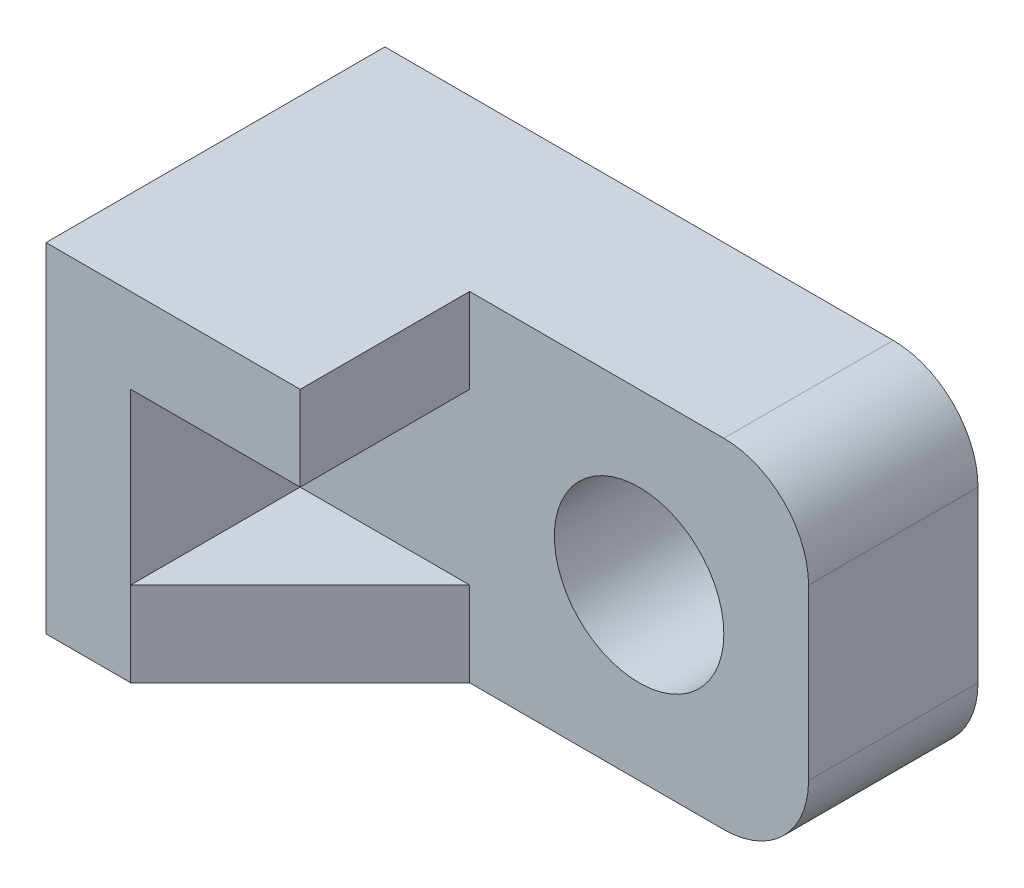
SolidWorks part; units mm, degrees
ref_plane "Front Plane" through (0, 0, 0) normal (0, 0, 1) x (1, 0, 0)
ref_plane "Top Plane" through (0, 0, 0) normal (0, 1, 0) x (1, 0, 0)
ref_plane "Right Plane" through (0, 0, 0) normal (1, 0, 0) x (0, 0, -1)
sketch "Sketch1" plane through (0, 0, 0) normal (0, 0, 1) x (1, 0, 0)
  line L0 (0, 20) -> (0, -20)
  line L1 (0, 20) -> (60, 20)
  line L2 (70, 10) -> (70, -10)
  line L3 (60, -20) -> (0, -20)
  arc A0 (70, 10) -> (60, 20) centre (60, 10) ccw
  arc A1 (60, -20) -> (70, -10) centre (60, -10) ccw
  circle A2 centre (50, 0) radius 10
  point P4 (0, 0)
  point P9 (70, 20)
  dimension "D3" = 10
  dimension "D4" = 10
  dimension "D5" = 50
  dimension "D1" = 40
  dimension "D2" = 70
extrude "Boss-Extrude1" add sketch "Sketch1" along normal blind 20
sketch "Sketch2" plane through (0, 0, 20) normal (0, 0, 1) x (1, 0, 0)
  line L0 (0, 20) -> (0, -20)
  line L1 (0, -20) -> (30, -20)
  line L2 (0, -20) -> (60, -20) construction
  line L3 (30, -20) -> (30, -10)
  line L4 (60, 20) -> (0, 20) construction
  line L5 (30, 20) -> (0, 20)
  line L6 (30, 10) -> (10, 10)
  line L7 (10, 10) -> (10, -10)
  line L8 (10, -10) -> (30, -10)
  line L10 (30, 10) -> (30, 20)
  dimension "D1" = 30
  dimension "D2" = 20
  dimension "D3" = 10
extrude "Boss-Extrude2" add sketch "Sketch2" along normal blind 20
sketch "Sketch3" plane through (0, -20, 0) normal (0, -1, 0) x (1, 0, 0)
  line L2 (0, 40) -> (30, 40) construction
  line L3 (10, 40) -> (30, 20)
  line L4 (10, 40) -> (30, 40)
  line L5 (30, 40) -> (30, 20)
extrude "Cut-Extrude1" cut sketch "Sketch3" against normal up to next
